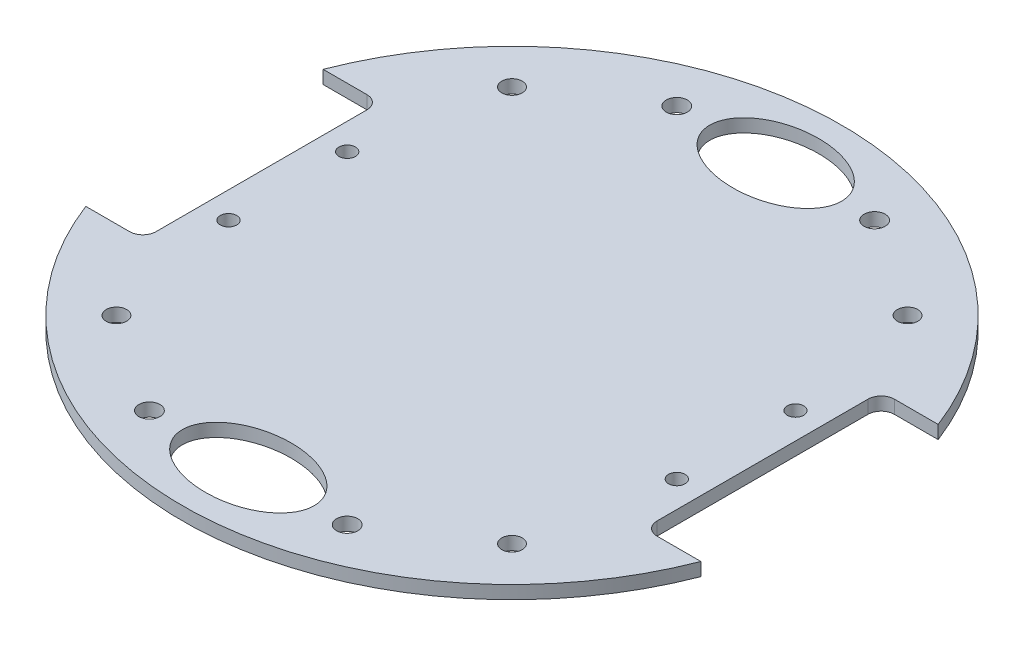
SolidWorks part; units mm, degrees
ref_plane "Plan de face" through (0, 0, 0) normal (0, 0, 1) x (1, 0, 0)
ref_plane "Plan de dessus" through (0, 0, 0) normal (0, 1, 0) x (1, 0, 0)
ref_plane "Plan de droite" through (0, 0, 0) normal (1, 0, 0) x (0, 0, -1)
sketch "Esquisse1" plane through (0, 0, 0) normal (0, 1, 0) x (1, 0, 0)
  line L0 (-46.6476, 18) -> (-40, 18)
  line L1 (-38, 16) -> (-38, -16)
  line L2 (-40, -18) -> (-46.6476, -18)
  line L3 (-50, 0) -> (50, 0) construction
  line L4 (0, 50) -> (0, -50) construction
  line L5 (40, -18) -> (46.6476, -18)
  line L6 (38, 16) -> (38, -16)
  line L7 (46.6476, 18) -> (40, 18)
  circle A0 centre (0, 0) radius 50 construction
  arc A1 (46.6476, 18) -> (-46.6476, 18) centre (0, 0) ccw
  arc A2 (-46.6476, -18) -> (46.6476, -18) centre (0, 0) ccw
  arc A3 (40, -18) -> (38, -16) centre (40, -16) cw
  arc A4 (38, 16) -> (40, 18) centre (40, 16) cw
  arc A5 (-40, 18) -> (-38, 16) centre (-40, 16) cw
  arc A6 (-38, -16) -> (-40, -18) centre (-40, -16) cw
  point P17 (38, -18)
  point P20 (38, 18)
  point P23 (-38, 18)
  point P26 (-38, -18)
  dimension "D1" = 100
  dimension "D5" = 2
  dimension "D2" = 18
  dimension "D3" = 18
  dimension "D4" = 38
extrude "Boss.-Extru.1" add sketch "Esquisse1" along normal blind 2 contours A1 L0 A5 L1 A6 L2 A2 L5 A3 L6 A4 L7
sketch "Esquisse2" plane through (0, 2, 0) normal (0, 1, 0) x (1, 0, 0)
  line L0 (-38, 0) -> (38, 0) construction
  line L1 (-38, 16) -> (-38, -16) construction
  line L2 (38, 16) -> (38, -16) construction
  line L3 (0, 50) -> (0, -50) construction
  arc A0 (46.6476, 18) -> (-46.6476, 18) centre (0, 0) ccw construction
  arc A1 (-46.6476, -18) -> (46.6476, -18) centre (0, 0) ccw construction
  ellipse E0 centre (0, 40) end of major axis (10, 40) minor radius 6.5
  ellipse E1 centre (0, -40) end of major axis (10, -40) minor radius 6.5
  dimension "D1" = 20
  dimension "D2" = 13
  dimension "D3" = 40
extrude "Enlèv. mat.-Extru.1" cut sketch "Esquisse2" against normal through all
sketch "Esquisse3" plane through (0, 2, 0) normal (0, 1, 0) x (1, 0, 0)
  line L0 (0, 50) -> (0, -50) construction
  line L1 (-38, 0) -> (38, 0) construction
  line L2 (-38, 16) -> (-38, -16) construction
  line L3 (38, 16) -> (38, -16) construction
  line L4 (-10, 40) -> (10, 40) construction
  circle A0 centre (-30, 30) radius 1.55
  arc A1 (46.6476, 18) -> (-46.6476, 18) centre (0, 0) ccw construction
  arc A2 (-46.6476, -18) -> (46.6476, -18) centre (0, 0) ccw construction
  circle A3 centre (30, 30) radius 1.55
  circle A4 centre (30, -30) radius 1.55
  circle A5 centre (-30, -30) radius 1.55
  circle A6 centre (-15, 40) radius 1.6
  circle A7 centre (15, 40) radius 1.6
  circle A8 centre (15, -40) radius 1.6
  circle A9 centre (-15, -40) radius 1.6
  circle A10 centre (-34, 9) radius 1.25
  circle A11 centre (-34, -9) radius 1.25
  circle A12 centre (34, -9) radius 1.25
  circle A13 centre (34, 9) radius 1.25
  ellipse E0 centre (0, 40) end of major axis (-10, 40) minor radius 6.5 construction
  dimension "D1" = 30
  dimension "D2" = 5
  dimension "D3" = 9
  dimension "25" = 30
  dimension "D4" = 4
extrude "Enlèv. mat.-Extru.2" cut sketch "Esquisse3" against normal blind 10
